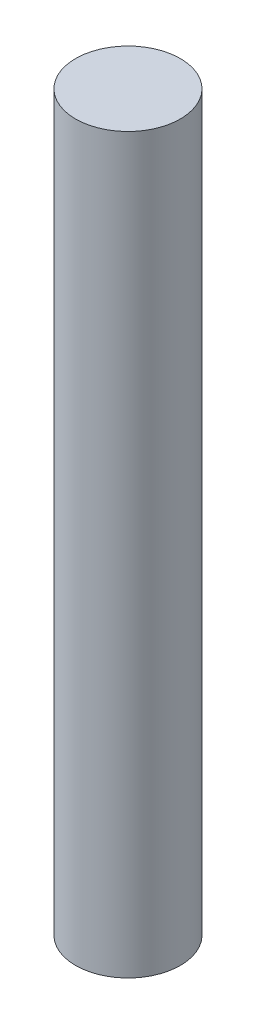
SolidWorks part; units mm, degrees
ref_plane "前视基准面" through (0, 0, 0) normal (0, 0, 1) x (1, 0, 0)
ref_plane "上视基准面" through (0, 0, 0) normal (0, 1, 0) x (1, 0, 0)
ref_plane "右视基准面" through (0, 0, 0) normal (1, 0, 0) x (0, 0, -1)
sketch "草图1" plane through (0, 0, 0) normal (0, 1, 0) x (1, 0, 0)
  circle A0 centre (0, 0) radius 2.5
  dimension "D1" = 5
extrude "凸台-拉伸1" add sketch "草图1" along normal blind 35
